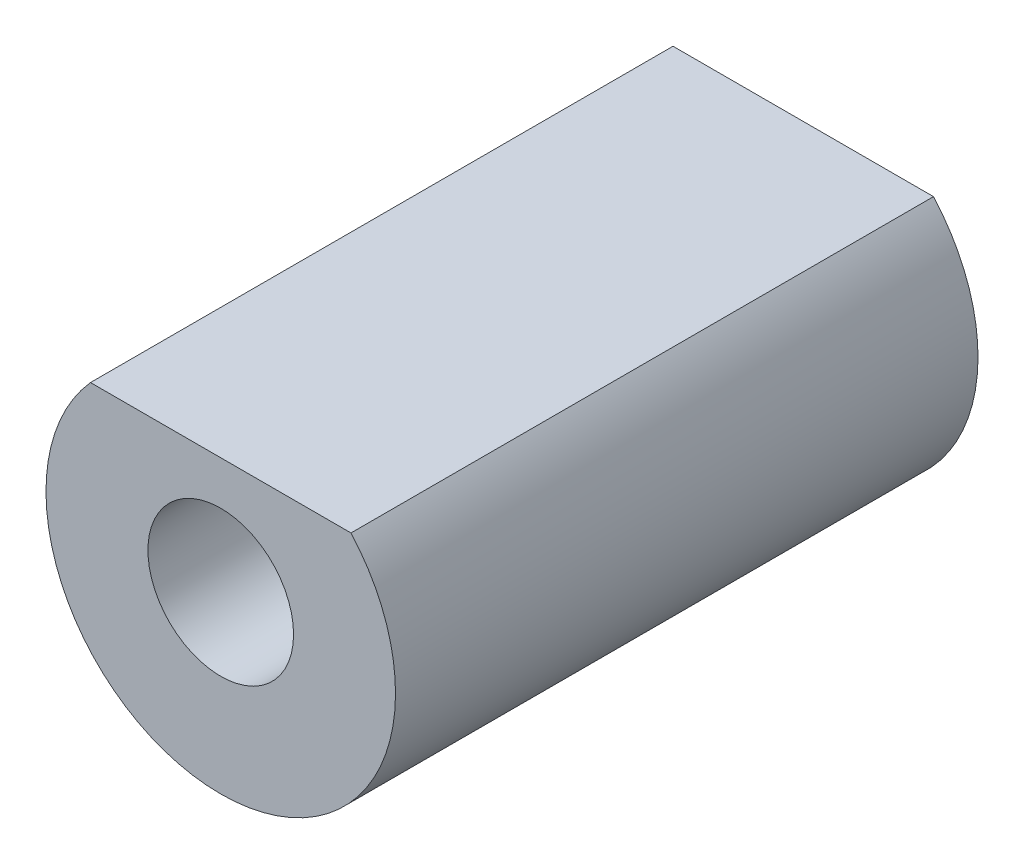
SolidWorks part; units mm, degrees
ref_plane "Front Plane" through (0, 0, 0) normal (0, 0, 1) x (1, 0, 0)
ref_plane "Top Plane" through (0, 0, 0) normal (0, 1, 0) x (1, 0, 0)
ref_plane "Right Plane" through (0, 0, 0) normal (1, 0, 0) x (0, 0, -1)
sketch "Sketch1" plane through (0, 0, 0) normal (0, 0, 1) x (1, 0, 0)
  line L0 (-2.2361, 2) -> (2.2361, 2)
  circle A0 centre (0, 0) radius 1.25
  arc A1 (-2.2361, 2) -> (2.2361, 2) centre (0, 0) ccw
  point P6 (0, 0)
  point P7 (3.0921, 3.7171)
  dimension "D1" = 2.5
  dimension "D2" = 3
  dimension "D3" = 2
extrude "Boss-Extrude1" add sketch "Sketch1" along normal blind 10
